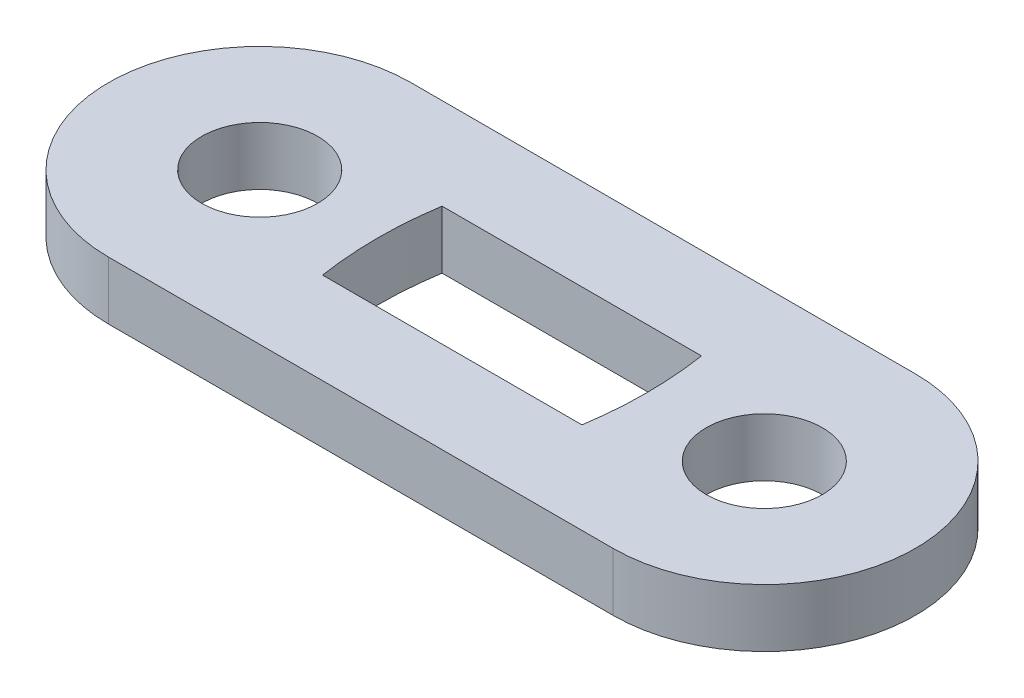
SolidWorks part; units mm, degrees
material "6061-T6 (SS)"
ref_plane "Front Plane" through (0, 0, 0) normal (0, 0, 1) x (1, 0, 0)
ref_plane "Top Plane" through (0, 0, 0) normal (0, 1, 0) x (1, 0, 0)
ref_plane "Right Plane" through (0, 0, 0) normal (1, 0, 0) x (0, 0, -1)
sketch "Sketch1" plane through (0, 0, 0) normal (0, 1, 0) x (1, 0, 0)
  line L0 (-6.9, 0) -> (6.9, 0) construction
  line L1 (6.9, 4.1337) -> (-6.9, 4.1337)
  line L3 (-6.9, -4.1337) -> (6.9, -4.1337)
  line L4 (3.5468, -1.6337) -> (-3.5468, -1.6337)
  line L5 (-3.5468, 1.6337) -> (3.5468, 1.6337)
  line L6 (6.9, 1.6337) -> (-6.9, 1.6337) construction
  line L7 (-6.9, -1.6337) -> (6.9, -1.6337) construction
  circle A0 centre (6.9, 0) radius 1.5875
  circle A1 centre (-6.9, 0) radius 1.5875
  arc A2 (-6.9, 4.1337) -> (-6.9, -4.1337) centre (-6.9, 0) ccw
  arc A3 (6.9, -4.1337) -> (6.9, 4.1337) centre (6.9, 0) ccw
  circle A4 centre (-9.4564, 0) radius 0.5953 construction
  circle A5 centre (-4.9564, 0) radius 0.5953 construction
  arc A6 (3.5468, 1.6337) -> (3.5468, -1.6337) centre (-6.9, 0) cw
  arc A7 (6.9, -1.6337) -> (6.9, 1.6337) centre (6.9, 0) ccw
  arc A8 (-6.9, 1.6337) -> (-6.9, -1.6337) centre (-6.9, 0) ccw construction
  arc A9 (-3.5468, 1.6337) -> (-3.5468, -1.6337) centre (6.9, 0) ccw
  point P3 (0, 0)
  dimension "D2" = 3.175
  dimension "D3" = 1.1906
  dimension "D4" = 4.5
  dimension "D1" = 13.8
  dimension "D5" = 2.5
  dimension "D6" = 2.5
extrude "Boss-Extrude2" add sketch "Sketch1" along normal mid plane 1.5875
sketch "Sketch2" plane through (0, -0.7937, 0) normal (0, -1, 0) x (-1, 0, 0)
  line L0 (6.9, 0) -> (-6.9, 0) construction
